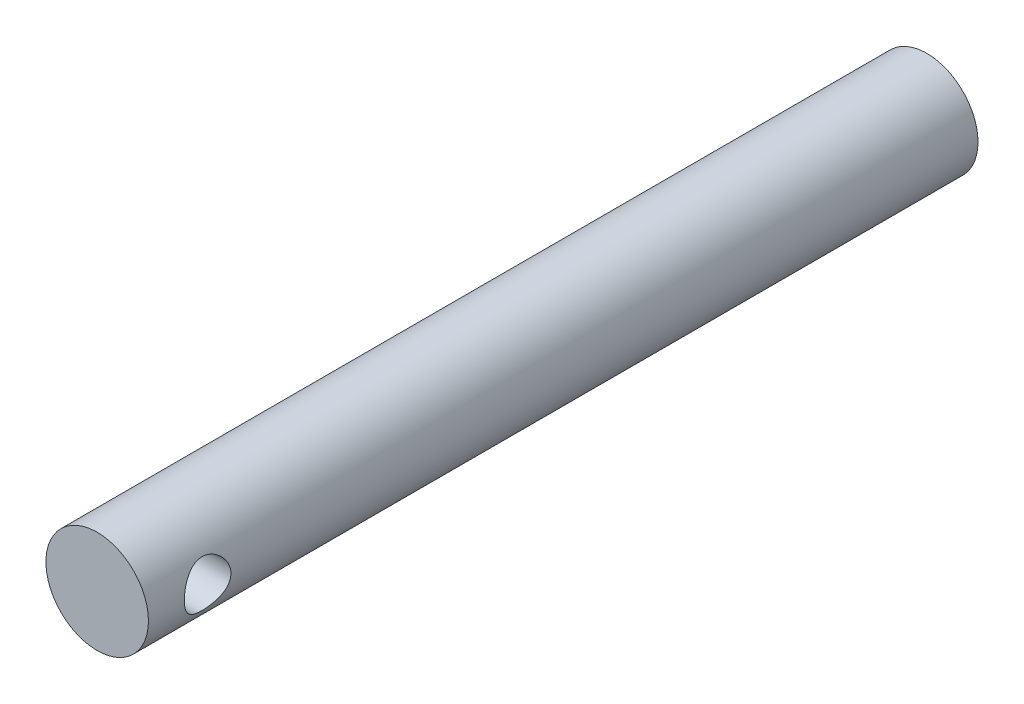
SolidWorks part; units mm, degrees
ref_plane "Front Plane" through (0, 0, 0) normal (0, 0, 1) x (1, 0, 0)
ref_plane "Top Plane" through (0, 0, 0) normal (0, 1, 0) x (1, 0, 0)
ref_plane "Right Plane" through (0, 0, 0) normal (1, 0, 0) x (0, 0, -1)
sketch "Sketch1" plane through (0, 0, 0) normal (0, 1, 0) x (1, 0, 0)
  line L1 (0, 0) -> (5.5, 0)
  line L2 (0, 0) -> (0, 89)
  line L3 (0, 89) -> (5.5, 89)
  line L4 (5.5, 0) -> (5.5, 89)
  dimension "D1" = 89
  dimension "D2" = 5.5
revolve "Revolve1" add sketch "Sketch1" angle 360 about L2
sketch "Sketch2" plane through (0, 0, 0) normal (1, 0, 0) x (0, 0, -1)
  circle A0 centre (6.35, 0) radius 2.5
  point P5 (0, 0)
  dimension "D1" = 5
  dimension "D2" = 6.35
extrude "Cut-Extrude1" cut sketch "Sketch2" against normal mid plane 30
hole_wizard "M6 Tapped Hole1" positions "Sketch3" profile "Sketch4" tap size "M6" standard "ISO"
sketch "Sketch3" plane through (0, 0, -89) normal (0, 0, -1) x (-1, 0, 0)
  point P0 (0, 0)
sketch "Sketch4" plane through (0, 0, -89) normal (1, 0, 0) x (0, 1, 0)
  line L0 (0, 0) -> (0, 31.4694)
  line L1 (0, 31.4694) -> (2.4455, 30)
  line L2 (2.4455, 30) -> (2.4455, 0)
  line L5 (2.4455, 0) -> (0, 0)
  line L10 (0, 31.4694) -> (-2.4455, 30) construction
  line L11 (0, -6.35) -> (0, 107.95) construction
  dimension "Tap Drill Dia." = 4.891
  dimension "Tap Drill Depth" = 30
  dimension "Drill Angle" = 118
cosmetic thread "Hole Thread1" parameters "D1"=25, "D2"=6
